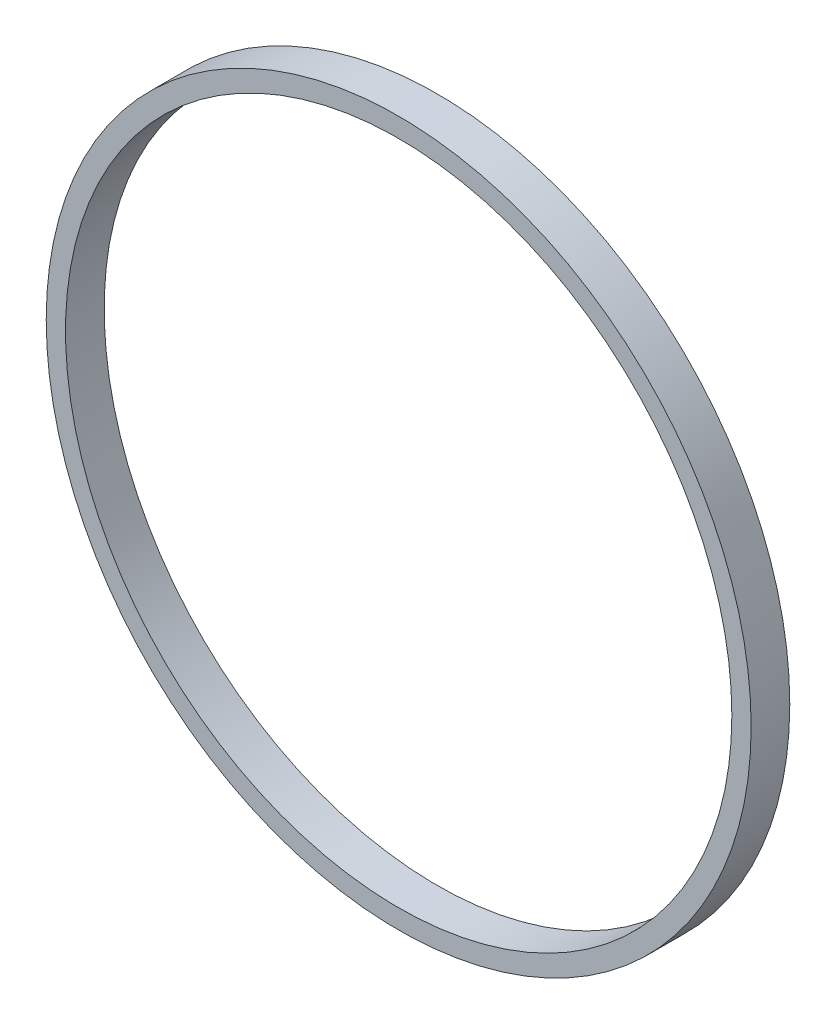
SolidWorks part; units mm, degrees
ref_plane "Front Plane" through (0, 0, 0) normal (0, 0, 1) x (1, 0, 0)
ref_plane "Top Plane" through (0, 0, 0) normal (0, 1, 0) x (1, 0, 0)
ref_plane "Right Plane" through (0, 0, 0) normal (1, 0, 0) x (0, 0, -1)
sketch "Sketch1" plane through (0, 0, 0) normal (0, 0, 1) x (1, 0, 0)
  circle A0 centre (0, 0) radius 43.815
  circle A1 centre (0, 0) radius 46.355
  dimension "D1" = 87.63
  dimension "D2" = 92.71
extrude "Boss-Extrude1" add sketch "Sketch1" along normal blind 5.08
